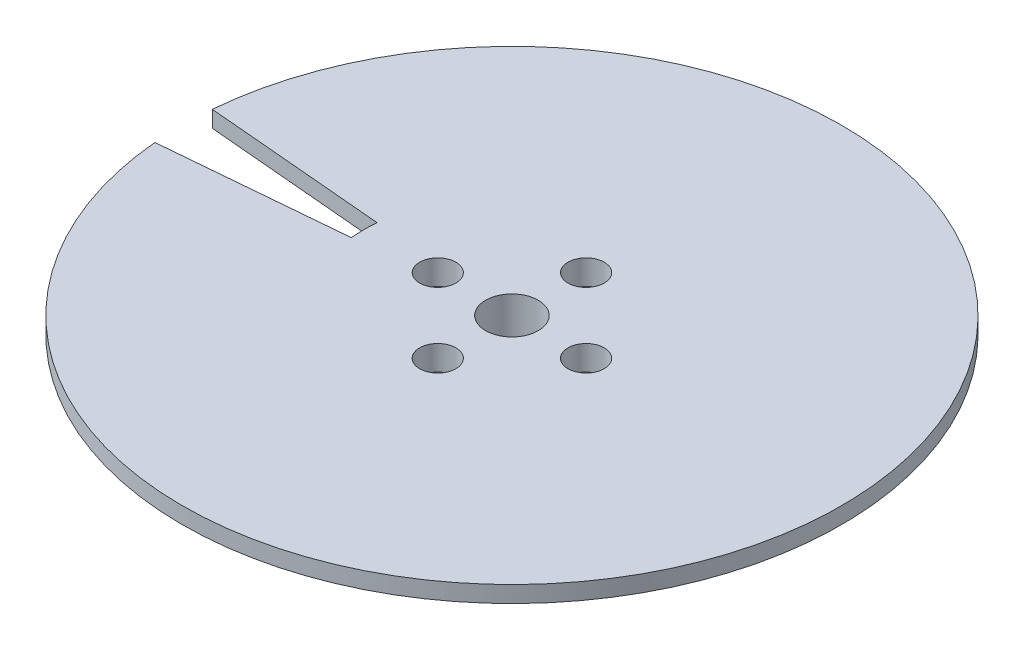
SolidWorks part; units mm, degrees
ref_plane "Front Plane" through (0, 0, 0) normal (0, 0, 1) x (1, 0, 0)
ref_plane "Top Plane" through (0, 0, 0) normal (0, 1, 0) x (1, 0, 0)
ref_plane "Right Plane" through (0, 0, 0) normal (1, 0, 0) x (0, 0, -1)
other "Configuration Table"
sketch "草图1" plane through (0, 0, 0) normal (0, 1, 0) x (1, 0, 0)
  circle A0 centre (0, 0) radius 7.5
  circle A1 centre (0, 0) radius 9
extrude "凸台-拉伸1" add sketch "草图1" along normal blind 6
sketch "草图2" plane through (0, 6, 0) normal (0, 1, 0) x (1, 0, 0)
  line L0 (0, 0) -> (-20, 0) construction
  line L1 (0, 0) -> (-19.9239, 1.7431)
  line L2 (0, 0) -> (-19.9239, -1.7431)
  circle A0 centre (0, 0) radius 20
  circle A2 centre (0, 0) radius 9
  dimension "D1" = 5
  dimension "D2" = 5
extrude "凸台-拉伸2" add sketch "草图2" against normal blind 1
sketch "草图4" plane through (0, 0, 0) normal (0, -1, 0) x (1, 0, 0)
  line L0 (0.9566, 6.3261) -> (0.8566, 6.3261) construction
  line L1 (0.9496, 7.3388) -> (0.9635, 5.3133) construction
  line L2 (-1.0434, 6.3123) -> (-0.9434, 6.3123) construction
  line L3 (-1.0364, 5.2996) -> (-1.0504, 7.3251) construction
  line L4 (0.8566, 6.3261) -> (0.8566, 7.4509)
  line L5 (0.8566, 6.3261) -> (0.8566, 5.4329)
  line L6 (-0.9434, 6.3123) -> (-0.9434, 7.4404)
  line L7 (-0.9434, 6.3123) -> (-0.9434, 5.4185)
  line L8 (6.3123, 0.9434) -> (5.4185, 0.9434)
  line L9 (6.3123, 0.9434) -> (7.4404, 0.9434)
  line L10 (6.3261, -0.8566) -> (7.4509, -0.8566)
  line L11 (6.3261, -0.8566) -> (5.4329, -0.8566)
  line L12 (0.9434, -6.3123) -> (0.9434, -5.4185)
  line L13 (0.9434, -6.3123) -> (0.9434, -7.4404)
  line L14 (-0.8566, -6.3261) -> (-0.8566, -7.4509)
  line L15 (-0.8566, -6.3261) -> (-0.8566, -5.4329)
  line L16 (-6.3123, -0.9434) -> (-5.4185, -0.9434)
  line L17 (-6.3123, -0.9434) -> (-7.4404, -0.9434)
  line L18 (-6.3261, 0.8566) -> (-7.4509, 0.8566)
  line L19 (-6.3261, 0.8566) -> (-5.4329, 0.8566)
  arc A0 (0.8566, 7.4509) -> (-0.9434, 7.4404) centre (0, 0) ccw
  arc A1 (0.8566, 5.4329) -> (-0.9434, 5.4185) centre (0, 0) ccw
  arc A2 (5.4329, -0.8566) -> (5.4185, 0.9434) centre (0, 0) ccw
  arc A3 (7.4509, -0.8566) -> (7.4404, 0.9434) centre (0, 0) ccw
  arc A4 (-0.8566, -5.4329) -> (0.9434, -5.4185) centre (0, 0) ccw
  arc A5 (-0.8566, -7.4509) -> (0.9434, -7.4404) centre (0, 0) ccw
  arc A6 (-5.4329, 0.8566) -> (-5.4185, -0.9434) centre (0, 0) ccw
  arc A7 (-7.4509, 0.8566) -> (-7.4404, -0.9434) centre (0, 0) ccw
  point P35 (0, 0)
  dimension "D1" = 4
extrude "凸台-拉伸3" add sketch "草图4" against normal blind 3
sketch "草图5" plane through (0, 6, 0) normal (0, 1, 0) x (1, 0, 0)
  circle A0 centre (0, 0) radius 7.5
extrude "凸台-拉伸4" add sketch "草图5" against normal blind 3
sketch "草图6" plane through (0, 6, 0) normal (0, 1, 0) x (1, 0, 0)
  circle A0 centre (0, 0) radius 1.6
extrude "切除-拉伸1" cut sketch "草图6" against normal blind 3
chamfer "倒角1" distance 1 angle 45 1 edges at (0, 0, 9)
sketch "草图14" plane through (0, 6, 0) normal (0, 1, 0) x (1, 0, 0)
  line L0 (0, 0) -> (0, 4.5) construction
  line L1 (0, 0) -> (4.5, 0) construction
  line L2 (0, 0) -> (0, -4.5) construction
  line L3 (0, 0) -> (-4.5, 0) construction
  circle A0 centre (0, 4.5) radius 1.1
  circle A1 centre (4.5, 0) radius 1.1
  circle A2 centre (0, -4.5) radius 1.1
  circle A3 centre (-4.5, 0) radius 1.1
  point P13 (0, 0)
  dimension "D1" = 4
extrude "切除-拉伸4" cut sketch "草图14" against normal blind 1.5
